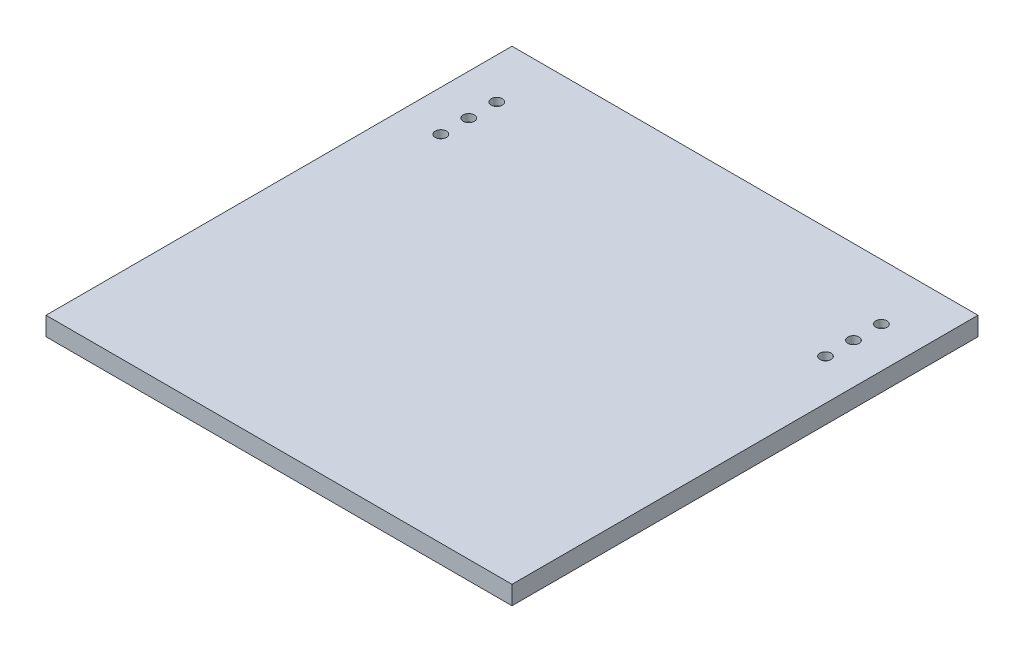
SolidWorks part; units mm, degrees
ref_plane "Front Plane" through (0, 0, 0) normal (0, 0, 1) x (1, 0, 0)
ref_plane "Top Plane" through (0, 0, 0) normal (0, 1, 0) x (1, 0, 0)
ref_plane "Right Plane" through (0, 0, 0) normal (1, 0, 0) x (0, 0, -1)
sketch "Sketch1" plane through (0, 0, 0) normal (0, 1, 0) x (1, 0, 0)
  line L1 (0, 0) -> (125, 0)
  line L2 (0, 0) -> (0, 125)
  line L3 (0, 125) -> (125, 125)
  line L4 (125, 0) -> (125, 125)
  dimension "D1" = 125
  dimension "D2" = 125
extrude "Boss-Extrude1" add sketch "Sketch1" along normal blind 5
sketch "Sketch2" plane through (0, 5, 0) normal (0, 1, 0) x (1, 0, 0)
  line L0 (10.91, 110) -> (114.09, 110) construction
  line L1 (125, 125) -> (0, 125) construction
  line L2 (10.91, 95) -> (114.09, 95) construction
  line L3 (10.91, 110) -> (10.91, 95) construction
  line L4 (114.09, 110) -> (114.09, 95) construction
  circle A0 centre (10.91, 95) radius 1.5
  circle A1 centre (10.91, 110) radius 1.5
  circle A2 centre (114.09, 110) radius 1.5
  circle A3 centre (114.09, 95) radius 1.5
  circle A4 centre (114.09, 102.5) radius 1.5
  circle A5 centre (10.91, 102.5) radius 1.5
  point P4 (62.5, 125)
  point P5 (62.5, 110)
  point P10 (62.5, 95)
  dimension "D4" = 3
  dimension "D1" = 15
  dimension "D2" = 103.18
  dimension "D3" = 15
extrude "Cut-Extrude1" cut sketch "Sketch2" against normal blind 2
hole_wizard "Tap Drill for M2x0.4 Tap1" positions "Sketch3" profile "Sketch5" hole size "M2x0.4" standard "ANSI Metric" end condition through all
sketch "Sketch3" plane through (0, 5, 0) normal (0, 1, 0) x (1, 0, 0)
  point P0 (10.91, 95)
  point P3 (10.91, 110)
  point P6 (114.09, 110)
  point P9 (114.09, 95)
  point P13 (10.91, 102.5)
  point P16 (114.09, 102.5)
sketch "Sketch5" plane through (10.91, 5, -95) normal (1, 0, 0) x (0, 0, 1)
  line L0 (0, 0) -> (0, 5)
  line L1 (0, 5) -> (0.8, 5)
  line L2 (0.8, 5) -> (0.8, 0.025)
  line L3 (0.8, 0.025) -> (0.825, 0)
  line L5 (0.825, 0) -> (0, 0)
  line L6 (-0.8, 0.025) -> (-0.825, 0) construction
  line L11 (0, -6.35) -> (0, 107.95) construction
  dimension "Thru Hole Dia." = 1.6
  dimension "Thru Hole Depth" = 5
  dimension "Near C'Sink Dia." = 1.65
  dimension "Near C'Sink Angle" = 90
